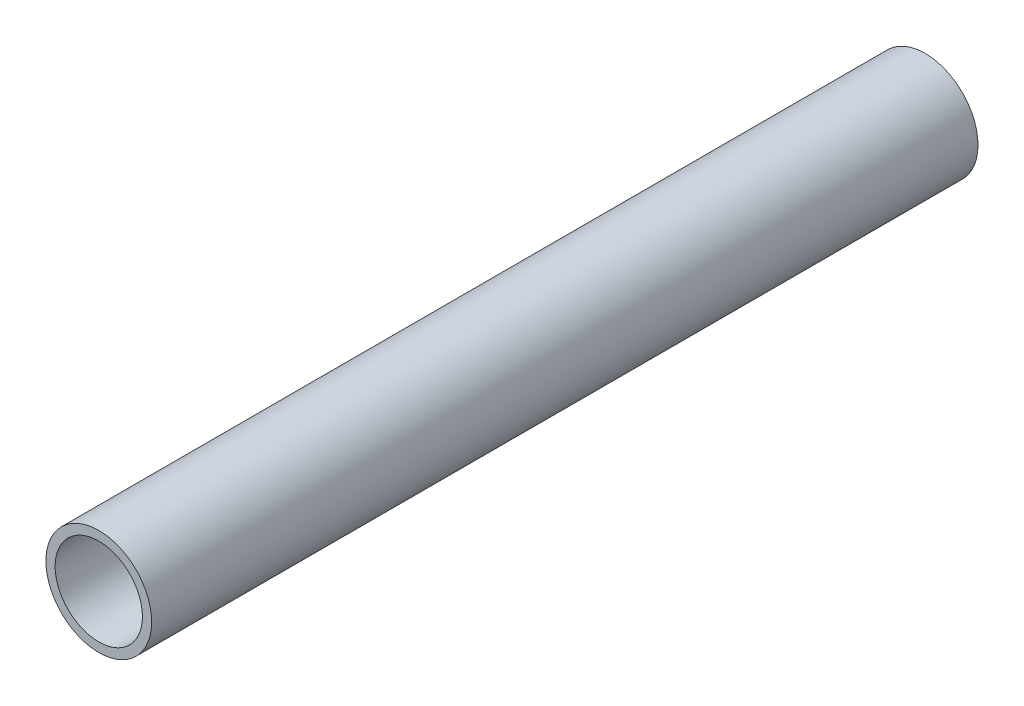
SolidWorks part; units mm, degrees
ref_plane "Спереди" through (0, 0, 0) normal (0, 0, 1) x (1, 0, 0)
ref_plane "Сверху" through (0, 0, 0) normal (0, 1, 0) x (1, 0, 0)
ref_plane "Справа" through (0, 0, 0) normal (1, 0, 0) x (0, 0, -1)
sketch "Эскиз1" plane through (0, 0, 0) normal (0, 0, 1) x (1, 0, 0)
  circle A0 centre (0, 0) radius 9
  circle A1 centre (0, 0) radius 10.9
extrude "Вытянуть1" add sketch "Эскиз1" along normal blind 170.35
